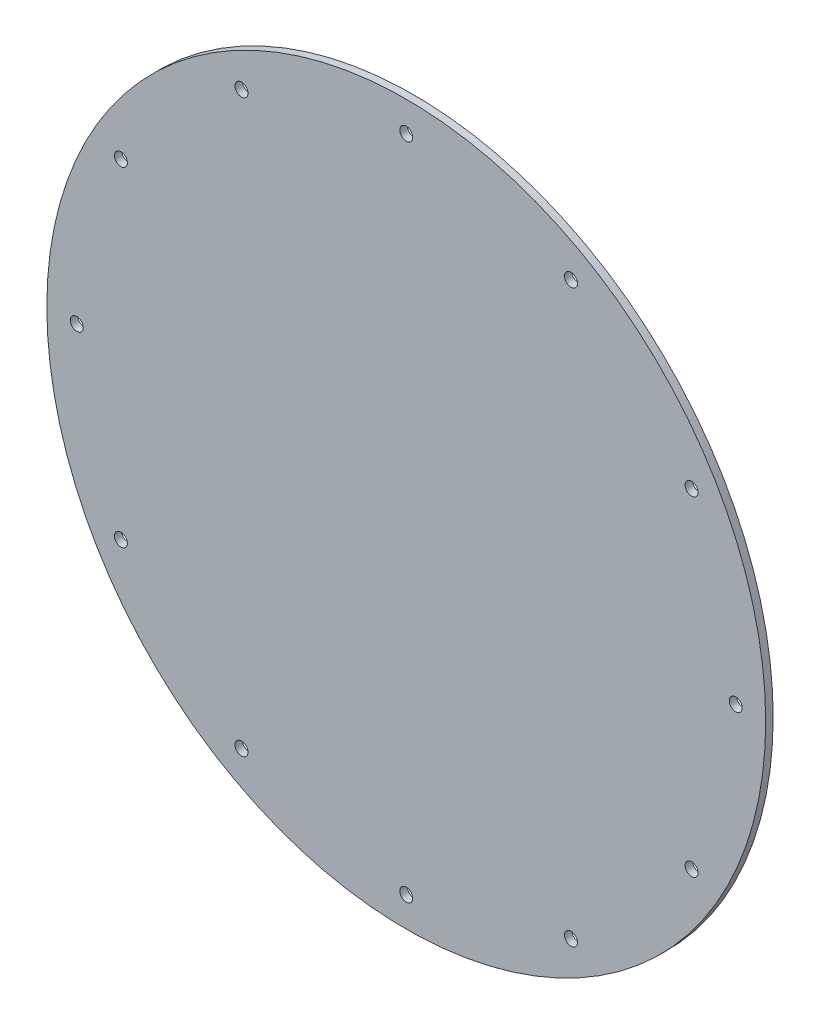
SolidWorks part; units mm, degrees
ref_plane "Front Plane" through (0, 0, 0) normal (0, 0, 1) x (1, 0, 0)
ref_plane "Top Plane" through (0, 0, 0) normal (0, 1, 0) x (1, 0, 0)
ref_plane "Right Plane" through (0, 0, 0) normal (1, 0, 0) x (0, 0, -1)
sketch "Sketch1" plane through (0, 0, 0) normal (0, 0, 1) x (1, 0, 0)
  circle A0 centre (0, 0) radius 609.6
  dimension "D1" = 1219.2
sketch "Sketch2" plane through (0, 0, 0) normal (0, 0, 1) x (1, 0, 0)
  line L0 (0, 508) -> (0, -508) construction
  line L1 (0, -508) -> (0, -609.6) construction
  line L2 (0, 508) -> (0, 609.6) construction
  circle A2 centre (0, 0) radius 609.6 construction
  circle A3 centre (0, 558.8) radius 11
  circle A4 centre (279.4, 483.935) radius 11
  circle A5 centre (483.935, 279.4) radius 11
  circle A6 centre (558.8, 0) radius 11
  circle A7 centre (483.935, -279.4) radius 11
  circle A8 centre (279.4, -483.935) radius 11
  circle A9 centre (0, -558.8) radius 11
  circle A10 centre (-279.4, -483.935) radius 11
  circle A11 centre (-483.935, -279.4) radius 11
  circle A12 centre (-558.8, 0) radius 11
  circle A13 centre (-483.935, 279.4) radius 11
  circle A14 centre (-279.4, 483.935) radius 11
  point P8 (0, 558.8)
  point P16 (0, 0)
  point P39 (0, 0)
  dimension "D1" = 101.6
  dimension "D2" = 22
  dimension "D4" = 101.6
  dimension "D3" = 12
extrude "Boss-Extrude1" add sketch "Sketch1" along normal blind 12.7
extrude "Cut-Extrude1" cut sketch "Sketch2" along direction (0, 0, 1) on the side of the normal up to surface (12.7 mm away)
